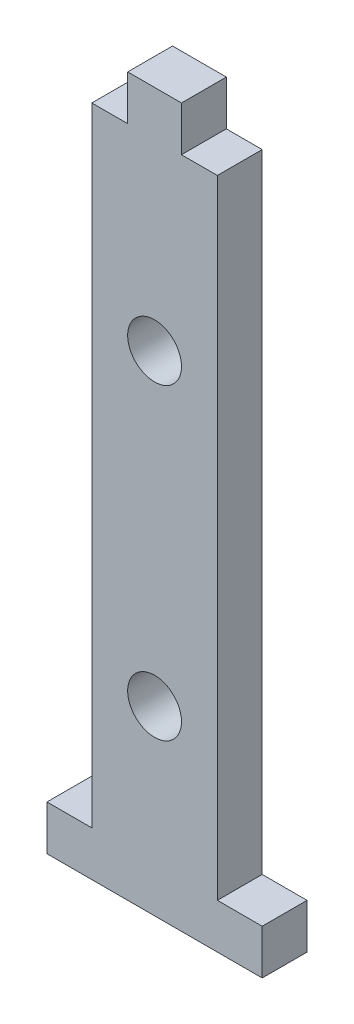
SolidWorks part; units mm, degrees
material "Beech"
ref_plane "Front" through (0, 0, 0) normal (0, 0, 1) x (1, 0, 0)
ref_plane "Top" through (0, 0, 0) normal (0, 1, 0) x (1, 0, 0)
ref_plane "Right" through (0, 0, 0) normal (1, 0, 0) x (0, 0, -1)
sketch "Sketch1" plane through (0, 0, 0) normal (0, 0, 1) x (1, 0, 0)
  line L0 (5.0219, 0) -> (-5.8147, 0) construction
  line L1 (-6, -20) -> (6, -20) construction
  line L2 (-6, -20) -> (-6, 20) construction
  line L3 (-6, 20) -> (6, 20) construction
  line L4 (6, -20) -> (6, 20) construction
  line L5 (-6, -20) -> (6, 20) construction
  line L6 (-6, 20) -> (6, -20) construction
  line L7 (0, 6.4542) -> (0, -5.8167) construction
  line L8 (6, 17.5) -> (-6, 17.5) construction
  line L9 (-3.5, 20) -> (-3.5, -20) construction
  line L10 (3.5, 20) -> (3.5, -20) construction
  line L11 (6, -17.5) -> (-6, -17.5) construction
  line L12 (1.5, 20) -> (-1.5, 20)
  line L13 (-1.5, 20) -> (-1.5, 17.5)
  line L14 (-1.5, 17.5) -> (-3.5, 17.5)
  line L15 (-3.5, 17.5) -> (-3.5, -17.5)
  line L16 (-3.5, -17.5) -> (-6, -17.5)
  line L17 (-6, -17.5) -> (-6, -20)
  line L18 (-6, -20) -> (6, -20)
  line L19 (6, -17.5) -> (6, -20)
  line L20 (3.5, -17.5) -> (6, -17.5)
  line L21 (3.5, 17.5) -> (3.5, -17.5)
  line L22 (1.5, 17.5) -> (3.5, 17.5)
  line L23 (1.5, 20) -> (1.5, 17.5)
  circle A0 centre (0, -9.88) radius 1.5
  circle A1 centre (0, 7.28) radius 1.5
  point P0 (0, 0)
  point P20 (0, -20)
  point P28 (0, 20)
  point P32 (0, 0)
  dimension "D6" = 3
  dimension "D1" = 40
  dimension "D2" = 2.5
  dimension "D3" = 2.5
  dimension "D4" = 12
  dimension "D5" = 4
  dimension "D7" = 7.62
  dimension "D8" = 24.78
extrude "Boss-Extrude1" add sketch "Sketch1" along normal blind 2.5
